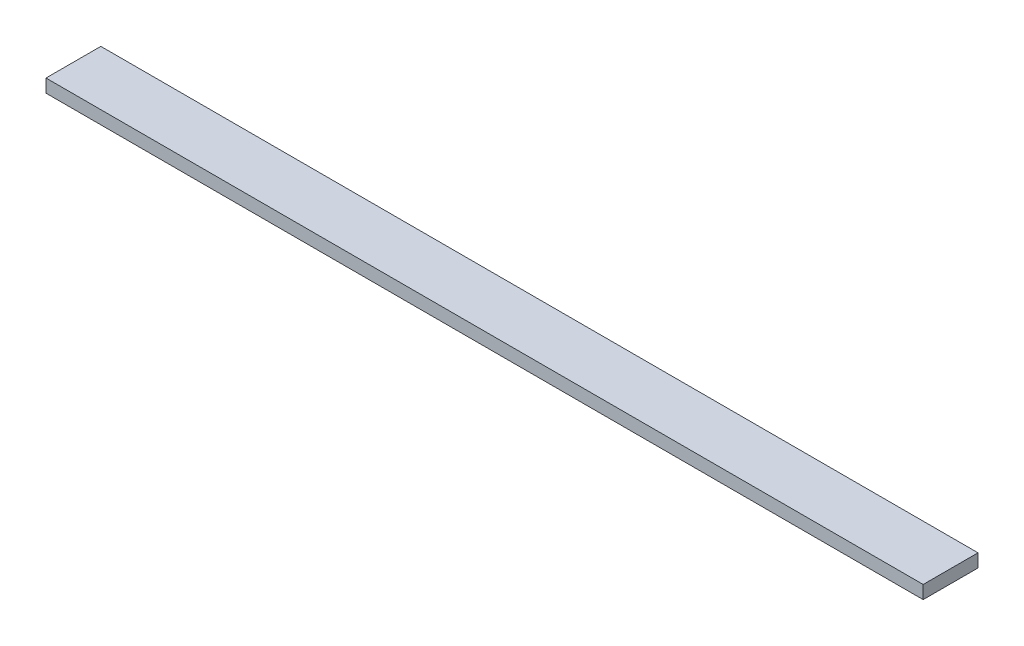
SolidWorks part; units mm, degrees
material "Pine"
ref_plane "Front Plane" through (0, 0, 0) normal (0, 0, 1) x (1, 0, 0)
ref_plane "Top Plane" through (0, 0, 0) normal (0, 1, 0) x (1, 0, 0)
ref_plane "Right Plane" through (0, 0, 0) normal (1, 0, 0) x (0, 0, -1)
sketch "Sketch1" plane through (0, 0, 0) normal (1, 0, 0) x (0, 0, -1)
  line L1 (0, 0) -> (-75, 0)
  line L2 (0, 0) -> (0, 18)
  line L3 (0, 18) -> (-75, 18)
  line L4 (-75, 0) -> (-75, 18)
  dimension "D1" = 18
  dimension "D2" = 75
extrude "Boss-Extrude1" add sketch "Sketch1" along normal blind 1200
